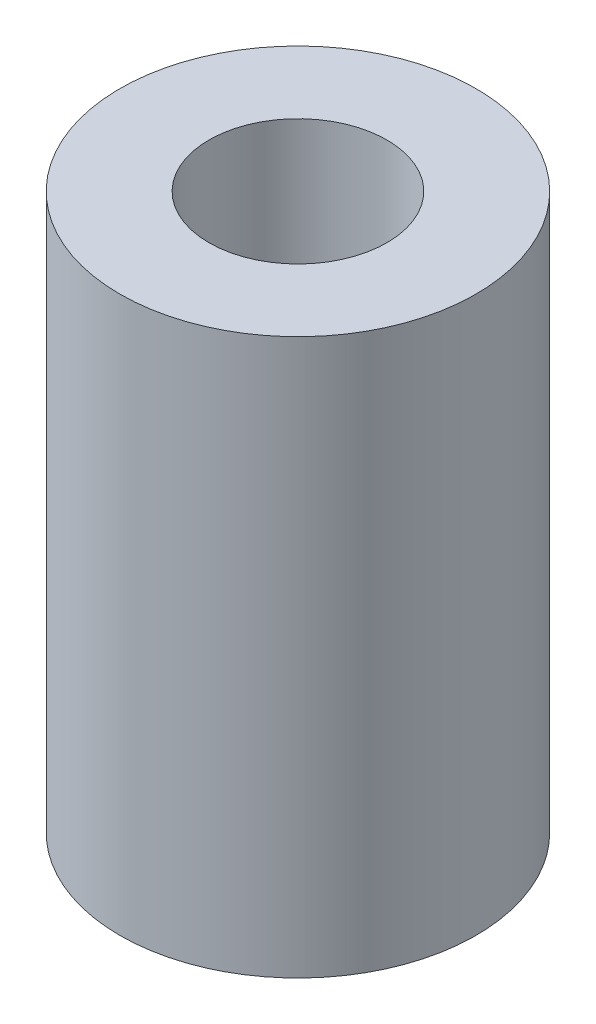
SolidWorks part; units mm, degrees
ref_plane "Front Plane" through (0, 0, 0) normal (0, 0, 1) x (1, 0, 0)
ref_plane "Top Plane" through (0, 0, 0) normal (0, 1, 0) x (1, 0, 0)
ref_plane "Right Plane" through (0, 0, 0) normal (1, 0, 0) x (0, 0, -1)
sketch "Sketch1" plane through (0, 0, 0) normal (0, 1, 0) x (1, 0, 0)
  circle A0 centre (0, 0) radius 3.175
  circle A1 centre (0, 0) radius 6.35
  dimension "D1" = 6.35
  dimension "D2" = 12.7
extrude "Boss-Extrude1" add sketch "Sketch1" along normal blind 19.812
